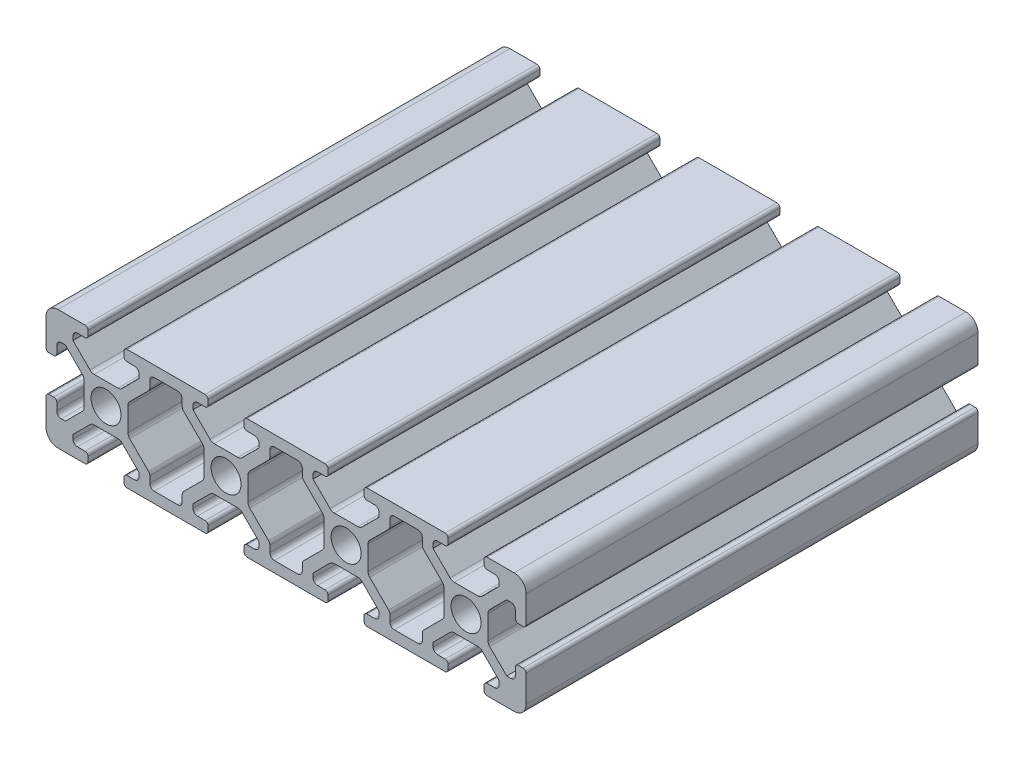
SolidWorks part; units mm, degrees
ref_plane "Front Plane" through (0, 0, 0) normal (0, 0, 1) x (1, 0, 0)
ref_plane "Top Plane" through (0, 0, 0) normal (0, 1, 0) x (1, 0, 0)
ref_plane "Right Plane" through (0, 0, 0) normal (1, 0, 0) x (0, 0, -1)
sketch "Sketch1" plane through (0, 0, 0) normal (0, 0, 1) x (1, 0, 0)
  line L0 (-37.6392, -10.3608) -> (-33.1392, -10.3608)
  line L1 (40.3608, -8.3608) -> (40.3608, -3.8608)
  line L2 (38.3608, 9.6392) -> (33.8608, 9.6392)
  line L3 (-39.6392, 7.6392) -> (-39.6392, 3.1392)
  line L4 (-6.6392, 9.1392) -> (-6.6392, 8.3392)
  line L5 (-12.6392, 9.1392) -> (-12.6392, 8.3392)
  line L6 (-32.6392, 9.1392) -> (-32.6392, 8.3392)
  line L7 (-26.6392, 9.1392) -> (-26.6392, 8.3392)
  line L8 (-33.1392, 9.6392) -> (-37.6392, 9.6392)
  line L9 (13.3608, 9.1392) -> (13.3608, 8.3392)
  line L10 (7.3608, 9.1392) -> (7.3608, 8.3392)
  line L11 (33.3608, 9.1392) -> (33.3608, 8.3392)
  line L12 (27.3608, 9.1392) -> (27.3608, 8.3392)
  line L13 (-6.6392, -9.0608) -> (-6.6392, -9.8608)
  line L14 (-12.6392, -9.0608) -> (-12.6392, -9.8608)
  line L15 (13.3608, -9.0608) -> (13.3608, -9.8608)
  line L16 (7.3608, -9.0608) -> (7.3608, -9.8608)
  line L17 (33.3608, -9.0608) -> (33.3608, -9.8608)
  line L18 (27.3608, -9.0608) -> (27.3608, -9.8608)
  line L19 (-26.6392, -9.0608) -> (-26.6392, -9.8608)
  line L20 (-32.6392, -9.0608) -> (-32.6392, -9.8608)
  line L21 (-26.1392, 9.6392) -> (-13.1392, 9.6392) construction
  line L22 (-13.1392, 9.6392) -> (-26.1392, 9.6392)
  line L23 (6.8608, 9.6392) -> (-6.1392, 9.6392)
  line L24 (26.8608, 9.6392) -> (13.8608, 9.6392)
  line L25 (33.8608, -10.3608) -> (38.3608, -10.3608)
  line L26 (13.8608, -10.3608) -> (26.8608, -10.3608)
  line L27 (-6.1392, -10.3608) -> (6.8608, -10.3608)
  line L28 (-26.1392, -10.3608) -> (-13.1392, -10.3608)
  line L29 (39.8608, 2.6392) -> (39.0608, 2.6392)
  line L30 (39.8608, -3.3608) -> (39.0608, -3.3608)
  line L31 (-39.1392, 2.6392) -> (-38.3392, 2.6392)
  line L32 (-39.1392, -3.3608) -> (-38.3392, -3.3608)
  line L33 (-39.6392, -3.8608) -> (-39.6392, -8.3608)
  line L34 (40.3608, 3.1392) -> (40.3608, 7.6392)
  line L35 (-37.8392, 3.1392) -> (-37.8392, 4.3892)
  line L36 (-34.3892, 7.8392) -> (-33.1392, 7.8392)
  line L37 (38.5608, 4.3892) -> (38.5608, 3.1392)
  line L38 (35.1108, -8.5608) -> (33.8608, -8.5608)
  line L39 (-37.8392, -5.1108) -> (-37.8392, -3.8608)
  line L40 (-26.1392, 7.8392) -> (-24.8892, 7.8392)
  line L41 (-33.1392, -8.5608) -> (-34.3892, -8.5608)
  line L42 (-6.1392, 7.8392) -> (-4.8892, 7.8392)
  line L43 (-13.1392, -8.5608) -> (-14.3892, -8.5608)
  line L44 (13.8608, 7.8392) -> (15.1108, 7.8392)
  line L45 (6.8608, -8.5608) -> (5.6108, -8.5608)
  line L46 (33.8608, 7.8392) -> (35.1108, 7.8392)
  line L47 (26.8608, -8.5608) -> (25.6108, -8.5608)
  line L48 (38.5608, -3.8608) -> (38.5608, -5.1108)
  line L49 (-26.9691, 3.5821) -> (-24.1392, 6.412)
  line L50 (-26.9691, -4.3037) -> (-24.1392, -7.1336)
  line L51 (-6.9691, 3.5821) -> (-4.1392, 6.412)
  line L52 (-5.6963, 2.3093) -> (-2.5589, 5.4467)
  line L53 (-12.3093, 3.5821) -> (-15.1392, 6.412)
  line L54 (-16.7195, 5.4467) -> (-13.5821, 2.3093)
  line L55 (-12.3093, -4.3037) -> (-15.1392, -7.1336)
  line L56 (-16.7195, -6.1684) -> (-13.5821, -3.0309)
  line L57 (7.6907, 3.5821) -> (4.8608, 6.412)
  line L58 (3.2805, 5.4467) -> (6.4179, 2.3093)
  line L59 (7.6907, -4.3037) -> (4.8608, -7.1336)
  line L60 (3.2805, -6.1684) -> (6.4179, -3.0309)
  line L61 (27.6907, 3.5821) -> (24.8608, 6.412)
  line L62 (23.2805, 5.4467) -> (26.4179, 2.3093)
  line L63 (27.6907, -4.3037) -> (24.8608, -7.1336)
  line L64 (23.2805, -6.1684) -> (26.4179, -3.0309)
  line L65 (-5.6963, -3.0309) -> (-2.5589, -6.1684)
  line L66 (-25.6963, 2.3093) -> (-22.5589, 5.4467)
  line L67 (-33.5821, -3.0309) -> (-36.412, -5.8608)
  line L68 (-32.3093, -4.3037) -> (-35.1392, -7.1336)
  line L69 (-32.3093, 3.5821) -> (-35.1392, 6.412)
  line L70 (-6.9691, -4.3037) -> (-4.1392, -7.1336)
  line L71 (-25.6963, -3.0309) -> (-22.5589, -6.1684)
  line L72 (13.0309, 3.5821) -> (15.8608, 6.412)
  line L73 (-33.5821, 2.3093) -> (-36.412, 5.1392)
  line L74 (14.3037, 2.3093) -> (17.4411, 5.4467)
  line L75 (14.3037, -3.0309) -> (17.4411, -6.1684)
  line L76 (13.0309, -4.3037) -> (15.8608, -7.1336)
  line L77 (33.0309, 3.5821) -> (35.8608, 6.412)
  line L78 (34.3037, 2.3093) -> (37.1336, 5.1392)
  line L79 (34.3037, -3.0309) -> (37.1336, -5.8608)
  line L80 (33.0309, -4.3037) -> (35.8608, -7.1336)
  line L81 (-11.6022, 3.2892) -> (-7.6762, 3.2892)
  line L82 (-21.5892, 7.8392) -> (-17.6892, 7.8392)
  line L83 (-24.8892, -8.5608) -> (-26.1392, -8.5608)
  line L84 (-24.1392, 7.0892) -> (-24.1392, 6.412)
  line L85 (-4.8892, -8.5608) -> (-6.1392, -8.5608)
  line L86 (-35.1392, 7.0892) -> (-35.1392, 6.412)
  line L87 (15.1108, -8.5608) -> (13.8608, -8.5608)
  line L88 (-15.1392, 7.0892) -> (-15.1392, 6.412)
  line L89 (-14.3892, 7.8392) -> (-13.1392, 7.8392)
  line L90 (5.6108, 7.8392) -> (6.8608, 7.8392)
  line L91 (-5.9892, 1.6022) -> (-5.9892, -2.3238)
  line L92 (-7.6762, -4.0108) -> (-11.6022, -4.0108)
  line L93 (-13.2892, -2.3238) -> (-13.2892, 1.6022)
  line L94 (25.6108, 7.8392) -> (26.8608, 7.8392)
  line L95 (4.8608, 7.0892) -> (4.8608, 6.412)
  line L96 (-4.1392, 7.0892) -> (-4.1392, 6.412)
  line L97 (-25.9892, 1.6022) -> (-25.9892, -2.3238)
  line L98 (-27.6762, -4.0108) -> (-31.6022, -4.0108)
  line L99 (-33.2892, -2.3238) -> (-33.2892, 1.6022)
  line L100 (-31.6022, 3.2892) -> (-27.6762, 3.2892)
  line L101 (8.3978, 3.2892) -> (12.3238, 3.2892)
  line L102 (14.0108, 1.6022) -> (14.0108, -2.3238)
  line L103 (12.3238, -4.0108) -> (8.3978, -4.0108)
  line L104 (6.7108, -2.3238) -> (6.7108, 1.6022)
  line L105 (28.3978, 3.2892) -> (32.3238, 3.2892)
  line L106 (34.0108, 1.6022) -> (34.0108, -2.3238)
  line L107 (32.3238, -4.0108) -> (28.3978, -4.0108)
  line L108 (26.7108, -2.3238) -> (26.7108, 1.6022)
  line L109 (24.8608, 7.0892) -> (24.8608, 6.412)
  line L110 (15.8608, 7.0892) -> (15.8608, 6.412)
  line L111 (-35.1392, -7.8108) -> (-35.1392, -7.1336)
  line L112 (35.8608, 7.0892) -> (35.8608, 6.412)
  line L113 (-15.1392, -7.8108) -> (-15.1392, -7.1336)
  line L114 (-24.1392, -7.8108) -> (-24.1392, -7.1336)
  line L115 (4.8608, -7.8108) -> (4.8608, -7.1336)
  line L116 (-4.1392, -7.8108) -> (-4.1392, -7.1336)
  line L117 (24.8608, -7.8108) -> (24.8608, -7.1336)
  line L118 (15.8608, -7.8108) -> (15.8608, -7.1336)
  line L119 (-37.0892, 5.1392) -> (-36.412, 5.1392)
  line L120 (35.8608, -7.8108) -> (35.8608, -7.1336)
  line L121 (-37.0892, -5.8608) -> (-36.412, -5.8608)
  line L122 (37.8108, 5.1392) -> (37.1336, 5.1392)
  line L123 (-22.3392, 7.0892) -> (-22.3392, 5.9771)
  line L124 (37.8108, -5.8608) -> (37.1336, -5.8608)
  line L125 (-16.9392, 7.0892) -> (-16.9392, 5.9771)
  line L126 (-1.5892, 7.8392) -> (2.3108, 7.8392)
  line L127 (-2.3392, 7.0892) -> (-2.3392, 5.9771)
  line L128 (3.0608, 7.0892) -> (3.0608, 5.9771)
  line L129 (18.4108, 7.8392) -> (22.3108, 7.8392)
  line L130 (17.6608, 7.0892) -> (17.6608, 5.9771)
  line L131 (23.0608, 7.0892) -> (23.0608, 5.9771)
  line L132 (-22.3392, -6.6987) -> (-22.3392, -7.8108)
  line L133 (-21.5892, -8.5608) -> (-17.6892, -8.5608)
  line L134 (-16.9392, -7.8108) -> (-16.9392, -6.6987)
  line L135 (-2.3392, -6.6987) -> (-2.3392, -7.8108)
  line L136 (-1.5892, -8.5608) -> (2.3108, -8.5608)
  line L137 (3.0608, -7.8108) -> (3.0608, -6.6987)
  line L138 (17.6608, -6.6987) -> (17.6608, -7.8108)
  line L139 (18.4108, -8.5608) -> (22.3108, -8.5608)
  line L140 (23.0608, -7.8108) -> (23.0608, -6.6987)
  circle A0 centre (-29.6392, -0.3608) radius 2.5
  circle A1 centre (-9.6392, -0.3608) radius 2.5
  circle A2 centre (10.3608, -0.3608) radius 2.5
  circle A3 centre (30.3608, -0.3608) radius 2.5
  arc A4 (38.3608, -10.3608) -> (40.3608, -8.3608) centre (38.3608, -8.3608) ccw
  arc A5 (40.3608, 7.6392) -> (38.3608, 9.6392) centre (38.3608, 7.6392) ccw
  arc A6 (-37.6392, -10.3608) -> (-39.6392, -8.3608) centre (-37.6392, -8.3608) cw
  arc A7 (-37.6392, 9.6392) -> (-39.6392, 7.6392) centre (-37.6392, 7.6392) ccw
  arc A8 (-26.9691, 3.5821) -> (-27.6762, 3.2892) centre (-27.6762, 4.2892) cw
  arc A9 (-32.3093, 3.5821) -> (-31.6022, 3.2892) centre (-31.6022, 4.2892) ccw
  arc A10 (-33.5821, 2.3093) -> (-33.2892, 1.6022) centre (-34.2892, 1.6022) cw
  arc A11 (-33.5821, -3.0309) -> (-33.2892, -2.3238) centre (-34.2892, -2.3238) ccw
  arc A12 (-32.3093, -4.3037) -> (-31.6022, -4.0108) centre (-31.6022, -5.0108) cw
  arc A13 (-26.9691, -4.3037) -> (-27.6762, -4.0108) centre (-27.6762, -5.0108) ccw
  arc A14 (-6.9691, -4.3037) -> (-7.6762, -4.0108) centre (-7.6762, -5.0108) ccw
  arc A15 (-12.3093, -4.3037) -> (-11.6022, -4.0108) centre (-11.6022, -5.0108) cw
  arc A16 (-12.3093, 3.5821) -> (-11.6022, 3.2892) centre (-11.6022, 4.2892) ccw
  arc A17 (-6.9691, 3.5821) -> (-7.6762, 3.2892) centre (-7.6762, 4.2892) cw
  arc A18 (7.6907, -4.3037) -> (8.3978, -4.0108) centre (8.3978, -5.0108) cw
  arc A19 (13.0309, -4.3037) -> (12.3238, -4.0108) centre (12.3238, -5.0108) ccw
  arc A20 (13.0309, 3.5821) -> (12.3238, 3.2892) centre (12.3238, 4.2892) cw
  arc A21 (7.6907, 3.5821) -> (8.3978, 3.2892) centre (8.3978, 4.2892) ccw
  arc A22 (33.0309, 3.5821) -> (32.3238, 3.2892) centre (32.3238, 4.2892) cw
  arc A23 (27.6907, 3.5821) -> (28.3978, 3.2892) centre (28.3978, 4.2892) ccw
  arc A24 (27.6907, -4.3037) -> (28.3978, -4.0108) centre (28.3978, -5.0108) cw
  arc A25 (33.0309, -4.3037) -> (32.3238, -4.0108) centre (32.3238, -5.0108) ccw
  arc A26 (34.3037, -3.0309) -> (34.0108, -2.3238) centre (35.0108, -2.3238) cw
  arc A27 (34.3037, 2.3093) -> (34.0108, 1.6022) centre (35.0108, 1.6022) ccw
  arc A28 (26.4179, -3.0309) -> (26.7108, -2.3238) centre (25.7108, -2.3238) ccw
  arc A29 (26.4179, 2.3093) -> (26.7108, 1.6022) centre (25.7108, 1.6022) cw
  arc A30 (14.3037, -3.0309) -> (14.0108, -2.3238) centre (15.0108, -2.3238) cw
  arc A31 (14.3037, 2.3093) -> (14.0108, 1.6022) centre (15.0108, 1.6022) ccw
  arc A32 (38.5608, 4.3892) -> (37.8108, 5.1392) centre (37.8108, 4.3892) ccw
  arc A33 (35.8608, 7.0892) -> (35.1108, 7.8392) centre (35.1108, 7.0892) ccw
  arc A34 (38.5608, -5.1108) -> (37.8108, -5.8608) centre (37.8108, -5.1108) cw
  arc A35 (35.8608, -7.8108) -> (35.1108, -8.5608) centre (35.1108, -7.8108) cw
  arc A36 (6.4179, -3.0309) -> (6.7108, -2.3238) centre (5.7108, -2.3238) ccw
  arc A37 (6.4179, 2.3093) -> (6.7108, 1.6022) centre (5.7108, 1.6022) cw
  arc A38 (-5.6963, -3.0309) -> (-5.9892, -2.3238) centre (-4.9892, -2.3238) cw
  arc A39 (-5.6963, 2.3093) -> (-5.9892, 1.6022) centre (-4.9892, 1.6022) ccw
  arc A40 (-25.6963, 2.3093) -> (-25.9892, 1.6022) centre (-24.9892, 1.6022) ccw
  arc A41 (-25.6963, -3.0309) -> (-25.9892, -2.3238) centre (-24.9892, -2.3238) cw
  arc A42 (-13.5821, -3.0309) -> (-13.2892, -2.3238) centre (-14.2892, -2.3238) ccw
  arc A43 (-13.5821, 2.3093) -> (-13.2892, 1.6022) centre (-14.2892, 1.6022) cw
  arc A44 (25.6108, -8.5608) -> (24.8608, -7.8108) centre (25.6108, -7.8108) cw
  arc A45 (22.3108, -8.5608) -> (23.0608, -7.8108) centre (22.3108, -7.8108) ccw
  arc A46 (17.6608, -7.8108) -> (18.4108, -8.5608) centre (18.4108, -7.8108) ccw
  arc A47 (15.1108, -8.5608) -> (15.8608, -7.8108) centre (15.1108, -7.8108) ccw
  arc A48 (5.6108, -8.5608) -> (4.8608, -7.8108) centre (5.6108, -7.8108) cw
  arc A49 (24.8608, 7.0892) -> (25.6108, 7.8392) centre (25.6108, 7.0892) cw
  arc A50 (22.3108, 7.8392) -> (23.0608, 7.0892) centre (22.3108, 7.0892) cw
  arc A51 (18.4108, 7.8392) -> (17.6608, 7.0892) centre (18.4108, 7.0892) ccw
  arc A52 (13.3608, 8.3392) -> (13.8608, 7.8392) centre (13.8608, 8.3392) ccw
  arc A53 (13.3608, 9.1392) -> (13.8608, 9.6392) centre (13.8608, 9.1392) cw
  arc A54 (27.3608, 8.3392) -> (26.8608, 7.8392) centre (26.8608, 8.3392) cw
  arc A55 (27.3608, 9.1392) -> (26.8608, 9.6392) centre (26.8608, 9.1392) ccw
  arc A56 (33.3608, 8.3392) -> (33.8608, 7.8392) centre (33.8608, 8.3392) ccw
  arc A57 (33.3608, 9.1392) -> (33.8608, 9.6392) centre (33.8608, 9.1392) cw
  arc A58 (39.0608, 2.6392) -> (38.5608, 3.1392) centre (39.0608, 3.1392) cw
  arc A59 (39.8608, 2.6392) -> (40.3608, 3.1392) centre (39.8608, 3.1392) ccw
  arc A60 (39.0608, -3.3608) -> (38.5608, -3.8608) centre (39.0608, -3.8608) ccw
  arc A61 (39.8608, -3.3608) -> (40.3608, -3.8608) centre (39.8608, -3.8608) cw
  arc A62 (33.3608, -9.8608) -> (33.8608, -10.3608) centre (33.8608, -9.8608) ccw
  arc A63 (33.3608, -9.0608) -> (33.8608, -8.5608) centre (33.8608, -9.0608) cw
  arc A64 (27.3608, -9.8608) -> (26.8608, -10.3608) centre (26.8608, -9.8608) cw
  arc A65 (27.3608, -9.0608) -> (26.8608, -8.5608) centre (26.8608, -9.0608) ccw
  arc A66 (13.3608, -9.8608) -> (13.8608, -10.3608) centre (13.8608, -9.8608) ccw
  arc A67 (13.3608, -9.0608) -> (13.8608, -8.5608) centre (13.8608, -9.0608) cw
  arc A68 (7.3608, -9.8608) -> (6.8608, -10.3608) centre (6.8608, -9.8608) cw
  arc A69 (7.3608, -9.0608) -> (6.8608, -8.5608) centre (6.8608, -9.0608) ccw
  arc A70 (-6.6392, -9.8608) -> (-6.1392, -10.3608) centre (-6.1392, -9.8608) ccw
  arc A71 (-6.6392, -9.0608) -> (-6.1392, -8.5608) centre (-6.1392, -9.0608) cw
  arc A72 (-12.6392, -9.8608) -> (-13.1392, -10.3608) centre (-13.1392, -9.8608) cw
  arc A73 (-12.6392, -9.0608) -> (-13.1392, -8.5608) centre (-13.1392, -9.0608) ccw
  arc A74 (7.3608, 8.3392) -> (6.8608, 7.8392) centre (6.8608, 8.3392) cw
  arc A75 (7.3608, 9.1392) -> (6.8608, 9.6392) centre (6.8608, 9.1392) ccw
  arc A76 (-6.6392, 8.3392) -> (-6.1392, 7.8392) centre (-6.1392, 8.3392) ccw
  arc A77 (-6.6392, 9.1392) -> (-6.1392, 9.6392) centre (-6.1392, 9.1392) cw
  arc A78 (-12.6392, 8.3392) -> (-13.1392, 7.8392) centre (-13.1392, 8.3392) cw
  arc A79 (-12.6392, 9.1392) -> (-13.1392, 9.6392) centre (-13.1392, 9.1392) ccw
  arc A80 (-26.6392, 8.3392) -> (-26.1392, 7.8392) centre (-26.1392, 8.3392) ccw
  arc A81 (-26.1392, 9.6392) -> (-26.6392, 9.1392) centre (-26.1392, 9.1392) ccw
  arc A82 (-26.6392, -9.8608) -> (-26.1392, -10.3608) centre (-26.1392, -9.8608) ccw
  arc A83 (-26.6392, -9.0608) -> (-26.1392, -8.5608) centre (-26.1392, -9.0608) cw
  arc A84 (-32.6392, -9.8608) -> (-33.1392, -10.3608) centre (-33.1392, -9.8608) cw
  arc A85 (-32.6392, -9.0608) -> (-33.1392, -8.5608) centre (-33.1392, -9.0608) ccw
  arc A86 (-39.6392, -3.8608) -> (-39.1392, -3.3608) centre (-39.1392, -3.8608) cw
  arc A87 (-38.3392, -3.3608) -> (-37.8392, -3.8608) centre (-38.3392, -3.8608) cw
  arc A88 (-39.6392, 3.1392) -> (-39.1392, 2.6392) centre (-39.1392, 3.1392) ccw
  arc A89 (-38.3392, 2.6392) -> (-37.8392, 3.1392) centre (-38.3392, 3.1392) ccw
  arc A90 (-33.1392, 9.6392) -> (-32.6392, 9.1392) centre (-33.1392, 9.1392) cw
  arc A91 (-32.6392, 8.3392) -> (-33.1392, 7.8392) centre (-33.1392, 8.3392) cw
  arc A92 (15.8608, 7.0892) -> (15.1108, 7.8392) centre (15.1108, 7.0892) ccw
  arc A93 (4.8608, 7.0892) -> (5.6108, 7.8392) centre (5.6108, 7.0892) cw
  arc A94 (-2.3392, -7.8108) -> (-1.5892, -8.5608) centre (-1.5892, -7.8108) ccw
  arc A95 (-1.5892, 7.8392) -> (-2.3392, 7.0892) centre (-1.5892, 7.0892) ccw
  arc A96 (2.3108, 7.8392) -> (3.0608, 7.0892) centre (2.3108, 7.0892) cw
  arc A97 (2.3108, -8.5608) -> (3.0608, -7.8108) centre (2.3108, -7.8108) ccw
  arc A98 (-4.8892, -8.5608) -> (-4.1392, -7.8108) centre (-4.8892, -7.8108) ccw
  arc A99 (-14.3892, -8.5608) -> (-15.1392, -7.8108) centre (-14.3892, -7.8108) cw
  arc A100 (-24.8892, -8.5608) -> (-24.1392, -7.8108) centre (-24.8892, -7.8108) ccw
  arc A101 (-34.3892, -8.5608) -> (-35.1392, -7.8108) centre (-34.3892, -7.8108) cw
  arc A102 (-37.0892, -5.8608) -> (-37.8392, -5.1108) centre (-37.0892, -5.1108) cw
  arc A103 (-37.8392, 4.3892) -> (-37.0892, 5.1392) centre (-37.0892, 4.3892) cw
  arc A104 (-15.1392, 7.0892) -> (-14.3892, 7.8392) centre (-14.3892, 7.0892) cw
  arc A105 (-4.8892, 7.8392) -> (-4.1392, 7.0892) centre (-4.8892, 7.0892) cw
  arc A106 (-17.6892, 7.8392) -> (-16.9392, 7.0892) centre (-17.6892, 7.0892) cw
  arc A107 (-21.5892, 7.8392) -> (-22.3392, 7.0892) centre (-21.5892, 7.0892) ccw
  arc A108 (-24.1392, 7.0892) -> (-24.8892, 7.8392) centre (-24.8892, 7.0892) ccw
  arc A109 (-34.3892, 7.8392) -> (-35.1392, 7.0892) centre (-34.3892, 7.0892) ccw
  arc A110 (23.0608, -6.6987) -> (23.2805, -6.1684) centre (23.8108, -6.6987) cw
  arc A111 (17.6608, -6.6987) -> (17.4411, -6.1684) centre (16.9108, -6.6987) ccw
  arc A112 (23.0608, 5.9771) -> (23.2805, 5.4467) centre (23.8108, 5.9771) ccw
  arc A113 (17.6608, 5.9771) -> (17.4411, 5.4467) centre (16.9108, 5.9771) cw
  arc A114 (3.0608, -6.6987) -> (3.2805, -6.1684) centre (3.8108, -6.6987) cw
  arc A115 (-2.3392, -6.6987) -> (-2.5589, -6.1684) centre (-3.0892, -6.6987) ccw
  arc A116 (3.0608, 5.9771) -> (3.2805, 5.4467) centre (3.8108, 5.9771) ccw
  arc A117 (-2.3392, 5.9771) -> (-2.5589, 5.4467) centre (-3.0892, 5.9771) cw
  arc A118 (-16.9392, 5.9771) -> (-16.7195, 5.4467) centre (-16.1892, 5.9771) ccw
  arc A119 (-22.3392, 5.9771) -> (-22.5589, 5.4467) centre (-23.0892, 5.9771) cw
  arc A120 (-22.3392, -6.6987) -> (-22.5589, -6.1684) centre (-23.0892, -6.6987) ccw
  arc A121 (-16.9392, -6.6987) -> (-16.7195, -6.1684) centre (-16.1892, -6.6987) cw
  arc A122 (-17.6892, -8.5608) -> (-16.9392, -7.8108) centre (-17.6892, -7.8108) ccw
  arc A123 (-22.3392, -7.8108) -> (-21.5892, -8.5608) centre (-21.5892, -7.8108) ccw
extrude "Boss-Extrude1" add sketch "Sketch1" along normal blind 75.3
